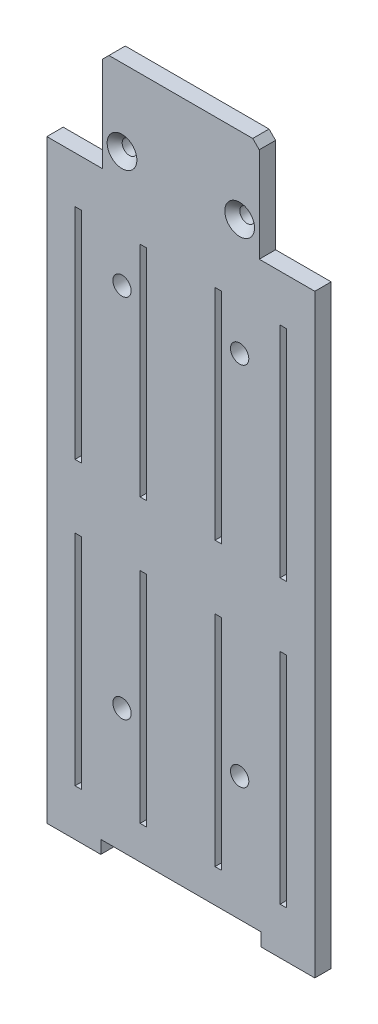
SolidWorks part; units mm, degrees
material "ABS"
ref_plane "Face" through (0, 0, 0) normal (0, 0, 1) x (1, 0, 0)
ref_plane "Dessus" through (0, 0, 0) normal (0, 1, 0) x (1, 0, 0)
ref_plane "Droite" through (0, 0, 0) normal (1, 0, 0) x (0, 0, -1)
sketch "Esquisse1" plane through (0, 0, 0) normal (0, 0, 1) x (1, 0, 0)
  line L1 (-41, -91) -> (-15.008, -91)
  line L2 (-41, -91) -> (-41, 91)
  line L3 (-41, 91) -> (-24, 91)
  line L4 (41, -91) -> (41, 91)
  line L5 (-41, -91) -> (41, 91) construction
  line L6 (-41, 91) -> (41, -91) construction
  line L8 (24, 91) -> (24, 122)
  line L9 (24, 122) -> (-24, 122)
  line L10 (-24, 91) -> (-24, 122)
  line L14 (24, 91) -> (41, 91)
  line L15 (0, 0) -> (41, 0) construction
  line L23 (-15.008, -91) -> (41, -91)
  point P0 (0, 0)
  point P6 (0, 122)
  dimension "D1" = 182
  dimension "D2" = 82
  dimension "D3" = 48
  dimension "D4" = 31
extrude "Boss.-Extru.1" add sketch "Esquisse1" along normal mid plane 5
sketch "Esquisse6" plane through (0, 0, 0) normal (1, 0, 0) x (0, 0, -1)
  line L0 (2.5, -91) -> (2.5, 91) construction
  line L9 (2.5, -57.9443) -> (2.5, -40.0557)
  line L10 (2.5, 54.0557) -> (2.5, 71.9443)
  arc A0 (2.5, 54.0557) -> (2.5, 71.9443) centre (1.5, 63) ccw
  arc A1 (2.5, -57.9443) -> (2.5, -40.0557) centre (1.5, -49) ccw
  dimension "D1" = 18
  dimension "D2" = 18
  dimension "D6" = 49
  dimension "D3" = 1
  dimension "D4" = 63
  dimension "D5" = 1
extrude "Boss.-Extru.2" add sketch "Esquisse6" along normal mid plane 61.18
sketch "Esquisse5" plane through (0, 0, 2.5) normal (0, 0, 1) x (1, 0, 0)
  line L0 (30.3815, -9.75) -> (30.3815, -76.75)
  line L6 (32.3815, 9.75) -> (30.3815, 9.75)
  line L23 (30.3815, 76.75) -> (32.3815, 76.75)
  line L31 (30.3815, 76.75) -> (30.3815, 9.75)
  line L32 (30.3815, -76.75) -> (32.3815, -76.75)
  line L33 (32.3815, 76.75) -> (32.3815, 9.75)
  line L35 (32.3815, -9.75) -> (30.3815, -9.75)
  line L37 (31.3815, 9.75) -> (31.3815, -9.75) construction
  line L39 (32.3815, -9.75) -> (32.3815, -76.75)
  point P10 (30.3815, 43.25)
  point P11 (30.3815, -43.25)
  dimension "D1" = 43.25
  dimension "D2" = 2
  dimension "D3" = 31.3815
  dimension "D5" = 43.25
  dimension "D6" = 67
  dimension "D4" = 67
extrude "Enlèv. mat.-Extru.1" cut sketch "Esquisse5" against normal through all and the other way through all
sketch "Esquisse7" plane through (0, 0, 0) normal (1, 0, 0) x (0, 0, -1)
  line L0 (2.5, -91) -> (2.5, 91) construction
  line L9 (2.5, -71.9443) -> (2.5, -54.0557)
  line L11 (2.5, 40.0557) -> (2.5, 57.9443)
  arc A0 (2.5, 40.0557) -> (2.5, 57.9443) centre (1.5, 49) ccw
  arc A1 (2.5, -71.9443) -> (2.5, -54.0557) centre (1.5, -63) ccw
  dimension "D1" = 18
  dimension "D4" = 18
  dimension "D2" = 49
  dimension "D3" = 1
  dimension "D5" = 63
  dimension "D6" = 1
extrude "Boss.-Extru.3" [suppressed] add sketch "Esquisse7" along normal mid plane 60.763
sketch "Esquisse14" plane through (0, 0, -2.5) normal (0, 0, -1) x (-1, 0, 0)
  line L0 (41, -91) -> (-41, -91) construction
  line L1 (-24.5, -91) -> (24.5, -91)
  line L2 (-24.5, -91) -> (-24.5, -87)
  line L3 (-24.5, -87) -> (24.5, -87)
  line L4 (24.5, -91) -> (24.5, -87)
  point P6 (0, -87)
  dimension "D1" = 4
  dimension "D2" = 49
extrude "Enlèv. mat.-Extru.5" cut sketch "Esquisse14" against normal through all
pattern_linear "Répétition linéaire2" count 2 spacing 19.921 along (-1, 0, 0) of "Enlèv. mat.-Extru.1"
sketch "Esquisse11" plane through (0, 0, 2.5) normal (0, 0, 1) x (1, 0, 0)
  line L0 (32.3815, 76.75) -> (30.3815, 76.75) construction
  line L1 (-1, 76.75) -> (1, 76.75)
  line L2 (-1, 76.75) -> (-1, -76.75)
  line L3 (-1, -76.75) -> (1, -76.75)
  line L4 (1, 76.75) -> (1, -76.75)
  line L5 (-1, 76.75) -> (1, -76.75) construction
  line L6 (-1, -76.75) -> (1, 76.75) construction
  point P0 (0, 0)
extrude "Enlèv. mat.-Extru.4" [suppressed] cut sketch "Esquisse11" against normal through all
sketch "Esquisse17" plane through (0, 0, 2.5) normal (0, 0, 1) x (1, 0, 0)
  line L0 (-18, 98.55) -> (18, 98.55) construction
  line L1 (24, 122) -> (-24, 122) construction
  line L2 (41, 91) -> (24, 91) construction
  circle A0 centre (18, 98.55) radius 2.25
  circle A1 centre (-18, 98.55) radius 2.25
  point P4 (0, 98.55)
  point P7 (0, 122)
  dimension "D1" = 4.5
  dimension "D2" = 36
  dimension "D3" = 7.55
extrude "Enlèv. mat.-Extru.7" cut sketch "Esquisse17" against normal blind 10
sketch "Esquisse15" plane through (0, 0, -2.5) normal (0, 0, -1) x (-1, 0, 0)
  line L0 (-24.5, -91) -> (-41, -91) construction
  line L1 (-27.5, -91) -> (27.5, -91)
  line L2 (-27.5, -91) -> (-27.5, -84)
  line L3 (-27.5, -84) -> (27.5, -84)
  line L4 (27.5, -91) -> (27.5, -84)
  line L5 (-24.5, -87) -> (-24.5, -91) construction
  line L6 (24.5, -87) -> (-24.5, -87) construction
  point P8 (0, -84)
  dimension "D1" = 3
  dimension "D2" = 3
extrude "Boss.-Extru.4" add sketch "Esquisse15" along normal blind 4
chamfer "Chanfrein3" distance 1 angle 45 6 edges at (-27.5, -87.5, -2.5) (0, -84, -2.5) (27.5, -87.5, -2.5) (0, -84, -6.5) (-27.5, -87.5, -6.5) (27.5, -87.5, -6.5)
chamfer "Chanfrein4" distance 2 angle 45 2 edges at (24, 122, 0) (-24, 122, 0)
sketch "Esquisse16" plane through (-41, 0, 0) normal (-1, 0, 0) x (0, 0, 1)
  line L0 (0, 0) -> (0, 60) construction
  circle A0 centre (0, 60) radius 1.1906
  dimension "D1" = 2.3813
  dimension "D2" = 60
extrude "Enlèv. mat.-Extru.6" [suppressed] cut sketch "Esquisse16" against normal blind 15
pattern_linear "Répétition linéaire1" [suppressed] count 3 spacing 15
mirror "Symétrie5" [suppressed] about plane through (0, 0, 0) normal (0, 1, 0)
mirror "Symétrie6" [suppressed] about plane through (0, 0, 0) normal (1, 0, 0)
sketch "Esquisse18" [suppressed] plane through (30.3815, 0, 0) normal (1, 0, 0) x (0, 0, -1)
  line L1 (2.5, -91) -> (2.5, 91) construction
  circle A0 centre (6, 49) radius 2.8
  circle A1 centre (6, -63) radius 2.8
  dimension "D1" = 5.6
  dimension "D4" = 63
  dimension "D2" = 3.5
  dimension "D3" = 49
extrude "Enlèv. mat.-Extru.8" [suppressed] cut sketch "Esquisse18" against normal blind 8
mirror "Symétrie7" [suppressed] about plane through (0, 0, 0) normal (1, 0, 0)
sketch "Esquisse19" plane through (30.3815, 0, 0) normal (1, 0, 0) x (0, 0, -1)
  line L0 (2.5, 9.75) -> (2.5, 76.75) construction
  line L3 (2.5, -76.75) -> (2.5, -9.75) construction
  circle A0 centre (6, 63) radius 2.8
  circle A1 centre (6, -49) radius 2.8
  arc A2 (2.5, 54.0557) -> (2.5, 71.9443) centre (1.5, 63) ccw construction
  arc A3 (2.5, -57.9443) -> (2.5, -40.0557) centre (1.5, -49) ccw construction
  point P9 (10.5, 63)
  point P16 (10.5, -49)
  dimension "D1" = 5.6
  dimension "D2" = 3.5
  dimension "D3" = 3.5
extrude "Enlèv. mat.-Extru.9" cut sketch "Esquisse19" against normal blind 8
mirror "Symétrie8" about plane through (0, 0, 0) normal (1, 0, 0) of "Enlèv. mat.-Extru.9"
chamfer "Chanfrein5" distance 2.3 angle 45 2 edges at (-15.75, 98.55, 2.5) (20.25, 98.55, 2.5)
mirror "Symétrie9" about plane through (0, 0, 0) normal (1, 0, 0) of "Répétition linéaire2", "Enlèv. mat.-Extru.1"
sketch "Esquisse20" plane through (0, 0, 2.5) normal (0, 0, 1) x (1, 0, 0)
  line L0 (-12.4605, -57.9443) -> (-30.3815, -57.9443) construction
  line L1 (-12.4605, -40.0557) -> (-30.3815, -40.0557) construction
  line L2 (-12.4605, -57.9443) -> (-30.3815, -57.9443) construction
  line L3 (-12.4605, -40.0557) -> (-30.3815, -40.0557) construction
  line L4 (-18, -49) -> (-18, -40.0557) construction
  line L5 (-18, -49) -> (-18, -57.9443) construction
  line L6 (-41, 91) -> (-41, -91) construction
  circle A0 centre (-18, -49) radius 2.8
  dimension "D2" = 5.6
  dimension "D1" = 23
extrude "Enlèv. mat.-Extru.10" cut sketch "Esquisse20" against normal blind 10
pattern_linear "Répétition linéaire3" count 2 spacing 36 along (1, 0, 0) count 2 spacing 112 along (0, 1, 0) of "Enlèv. mat.-Extru.10"
sketch "Esquisse21" [suppressed] plane through (0, 0, 2.5) normal (0, 0, 1) x (1, 0, 0)
  line L0 (-12.4605, -71.9443) -> (-30.3815, -71.9443) construction
  line L1 (-12.4605, -54.0557) -> (-30.3815, -54.0557) construction
  line L2 (-12.4605, -71.9443) -> (-30.3815, -71.9443) construction
  line L3 (-12.4605, -54.0557) -> (-30.3815, -54.0557) construction
  line L4 (-18, -63) -> (-18, -54.0557) construction
  line L5 (-18, -63) -> (-18, -71.9443) construction
  line L6 (-41, 91) -> (-41, -91) construction
  circle A0 centre (-18, -63) radius 2.8
  dimension "D1" = 5.6
  dimension "D2" = 23
extrude "Enlèv. mat.-Extru.11" [suppressed] cut sketch "Esquisse21" against normal blind 10
pattern_linear "Répétition linéaire4" [suppressed] count 2 spacing 36 count 2 spacing 112
